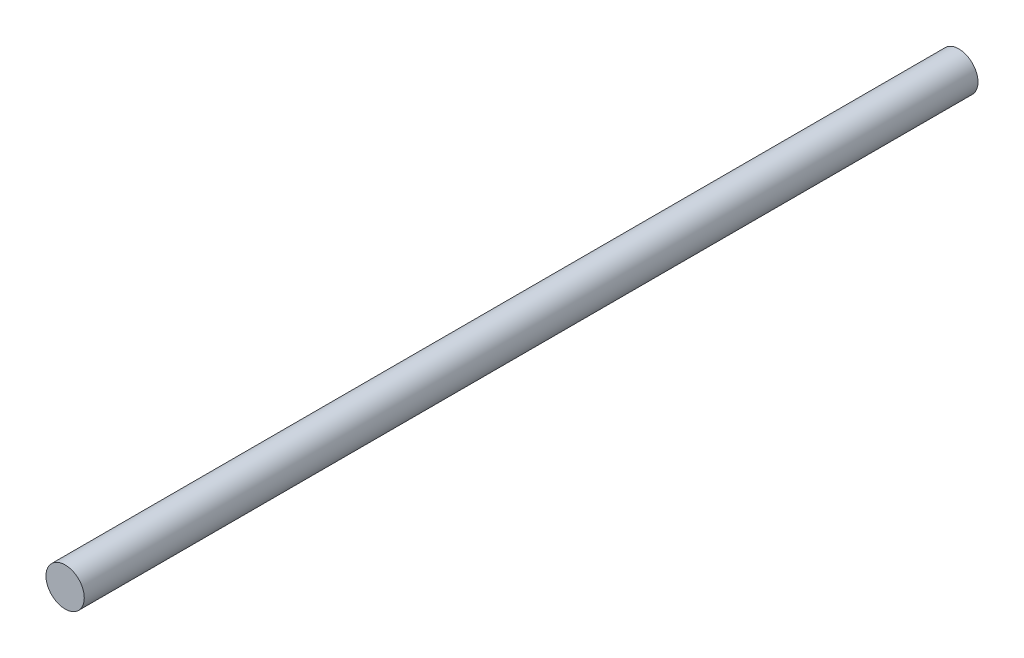
SolidWorks part; units mm, degrees
material "6061 合金"
ref_plane "前视基准面" through (0, 0, 0) normal (0, 0, 1) x (1, 0, 0)
ref_plane "上视基准面" through (0, 0, 0) normal (0, 1, 0) x (1, 0, 0)
ref_plane "右视基准面" through (0, 0, 0) normal (1, 0, 0) x (0, 0, -1)
sketch "草图1" plane through (0, 0, 0) normal (0, 0, 1) x (1, 0, 0)
  circle A0 centre (0, 0) radius 1.5
  dimension "D1" = 3
extrude "凸台-拉伸1" add sketch "草图1" along normal blind 70
cosmetic thread "装饰螺纹线1" parameters "D1"=15, "D2"=2
